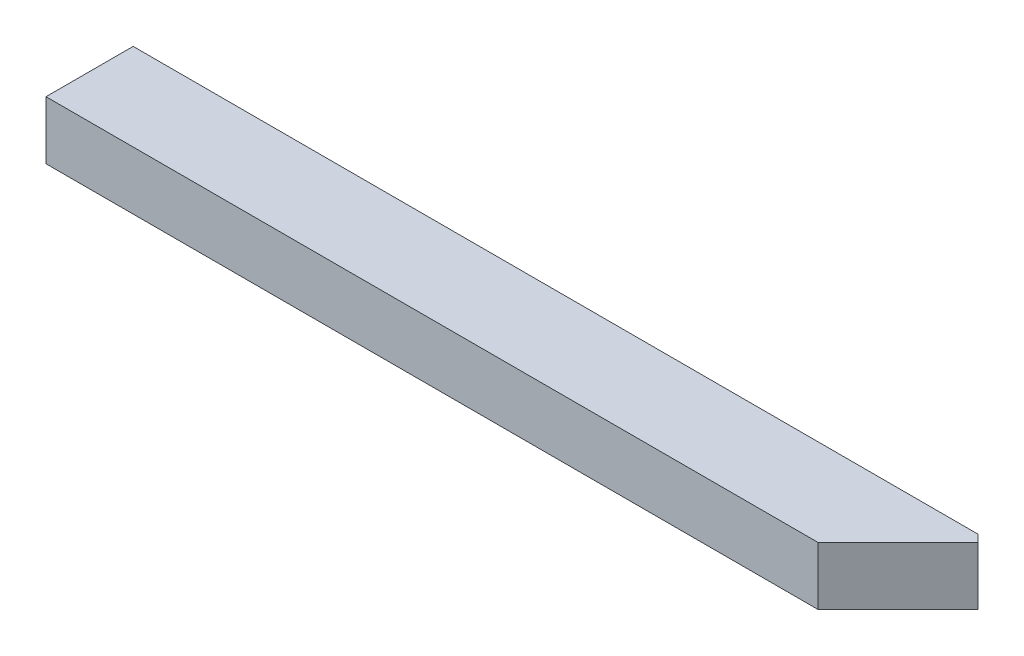
SolidWorks part; units mm, degrees
material "Pine"
ref_plane "X-Y Datum" through (0, 0, 0) normal (0, 0, 1) x (1, 0, 0)
ref_plane "X-Z Datum" through (0, 0, 0) normal (0, 1, 0) x (1, 0, 0)
ref_plane "Y-Z Datum" through (0, 0, 0) normal (1, 0, 0) x (0, 0, -1)
sketch "Sketch1" plane through (0, 0, 0) normal (1, 0, 0) x (0, 0, -1)
  line L1 (-12.7, 12.7) -> (12.7, 12.7)
  line L2 (-12.7, 12.7) -> (-12.7, -12.7)
  line L3 (-12.7, -12.7) -> (12.7, -12.7)
  line L4 (12.7, 12.7) -> (12.7, -12.7)
  line L5 (-12.7, 12.7) -> (12.7, -12.7) construction
  line L6 (-12.7, -12.7) -> (12.7, 12.7) construction
  point P0 (0, 0)
  dimension "D1" = 25.4
extrude "Boss-Extrude1" add sketch "Sketch1" along normal blind 350.2982
sketch "Sketch2" plane through (0, 12.7, 0) normal (0, 1, 0) x (1, 0, 0)
  line L0 (350.2982, -12.7) -> (372.5232, 9.525)
  line L1 (372.5232, 12.7) -> (350.2982, 12.7)
  line L2 (350.2982, 12.7) -> (350.2982, -12.7)
  line L3 (372.5232, 9.525) -> (372.5232, 12.7)
  dimension "D1" = 45
  dimension "D2" = 3.175
extrude "Boss-Extrude2" add sketch "Sketch2" against normal up to surface (25.4 mm away) up to face at (175.1491, -12.7, 0)
sketch "Sketch3" plane through (0, 12.7, 0) normal (0, 1, 0) x (1, 0, 0)
  line L0 (372.5232, 9.525) -> (369.3482, 12.7)
  line L1 (372.5232, 12.7) -> (0, 12.7) construction
  line L2 (350.2982, -12.7) -> (372.5232, 9.525) construction
  line L3 (369.3482, 12.7) -> (372.5232, 12.7)
  line L4 (372.5232, 12.7) -> (372.5232, 9.525)
extrude "Cut-Extrude1" cut sketch "Sketch3" against normal through all both and the other way through all
sketch "Sketch4" plane through (0, 12.7, 0) normal (0, 1, 0) x (1, 0, 0)
  line L0 (0, -12.7) -> (0, -25.4)
  line L1 (0, -25.4) -> (337.5982, -25.4)
  line L2 (337.5982, -25.4) -> (350.2982, -12.7)
  line L3 (350.2982, -12.7) -> (0, -12.7)
  line L4 (369.3482, 12.7) -> (0, 12.7) construction
  line L5 (350.2982, -12.7) -> (372.5232, 9.525) construction
  dimension "D1" = 38.1
extrude "Boss-Extrude3" add sketch "Sketch4" against normal up to surface (25.4 mm away) up to face at (218.4339, -12.7, -1.905)
